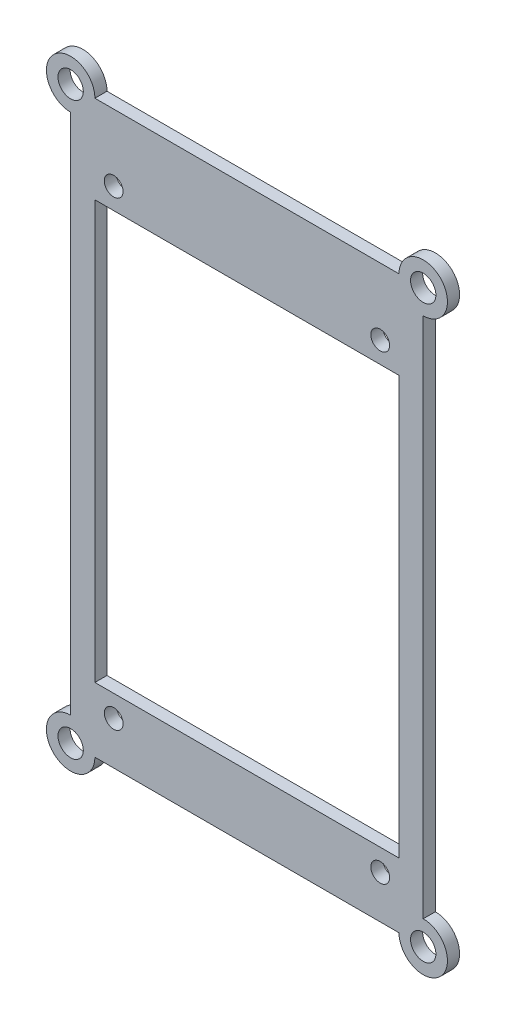
SolidWorks part; units mm, degrees
ref_plane "Front Plane" through (0, 0, 0) normal (0, 0, 1) x (1, 0, 0)
ref_plane "Top Plane" through (0, 0, 0) normal (0, 1, 0) x (1, 0, 0)
ref_plane "Right Plane" through (0, 0, 0) normal (1, 0, 0) x (0, 0, -1)
sketch "Sketch1" plane through (0, 0, 0) normal (0, 0, 1) x (1, 0, 0)
  line L1 (4.1232, -28.957) -> (4.1232, 57.243) construction
  line L2 (4.1232, 46.7259) -> (54.3232, 46.7259)
  line L3 (4.1232, 46.7259) -> (4.1232, -22.2741)
  line L8 (54.3232, 61.243) -> (4.1232, 61.243)
  line L9 (0.1232, 57.243) -> (0.1232, -28.957)
  line L10 (4.1232, -32.957) -> (54.3232, -32.957)
  line L11 (58.3232, -28.957) -> (58.3232, 57.243)
  line L12 (54.3232, 61.243) -> (4.1232, 61.243)
  line L13 (0.1232, 57.243) -> (0.1232, -28.957)
  line L14 (4.1232, -32.957) -> (54.3232, -32.957)
  line L15 (58.3232, -28.957) -> (58.3232, 57.243)
  line L16 (4.1232, -22.2741) -> (54.3232, -22.2741)
  line L17 (54.3232, 46.7259) -> (54.3232, -22.2741)
  line L18 (54.3232, -28.957) -> (54.3232, 57.243) construction
  circle A0 centre (7.2232, 50.2227) radius 1.55
  circle A1 centre (51.2232, 50.223) radius 1.55
  circle A2 centre (7.2331, -25.8573) radius 1.5527
  circle A3 centre (51.2232, -25.857) radius 1.55
  arc A4 (4.1232, 61.243) -> (0.1232, 57.243) centre (0.1232, 61.243) ccw
  arc A5 (0.1232, -28.957) -> (4.1232, -32.957) centre (0.1232, -32.957) ccw
  arc A6 (54.3232, -32.957) -> (58.3232, -28.957) centre (58.3232, -32.957) ccw
  arc A7 (58.3232, 57.243) -> (54.3232, 61.243) centre (58.3232, 61.243) ccw
  arc A17 (4.1232, 61.243) -> (0.1232, 57.243) centre (0.1232, 61.243) ccw
  arc A18 (0.1232, -28.957) -> (4.1232, -32.957) centre (0.1232, -32.957) ccw
  arc A19 (54.3232, -32.957) -> (58.3232, -28.957) centre (58.3232, -32.957) ccw
  arc A20 (58.3232, 57.243) -> (54.3232, 61.243) centre (58.3232, 61.243) ccw
  dimension "D1" = 69
  dimension "D2" = 0
  dimension "D3" = 50.2
extrude "Boss-Extrude1" add sketch "Sketch1" along normal blind 2
sketch "Sketch2" plane through (0, 0, 2) normal (0, 0, 1) x (1, 0, 0)
  circle A0 centre (0.1232, 61.243) radius 2.09
  circle A1 centre (58.3232, 61.243) radius 2.09
  circle A2 centre (0.1232, -32.957) radius 2.09
  circle A3 centre (58.3232, -32.957) radius 2.09
  dimension "D1" = 4.18
  dimension "D2" = 4.18
  dimension "D3" = 4.18
  dimension "D4" = 4.18
extrude "Cut-Extrude1" cut sketch "Sketch2" against normal blind 10
